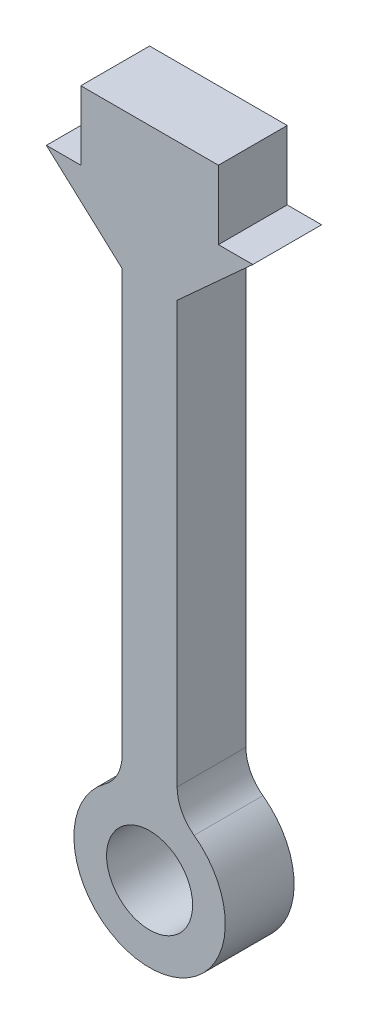
SolidWorks part; units mm, degrees
ref_plane "Plan de face" through (0, 0, 0) normal (0, 0, 1) x (1, 0, 0)
ref_plane "Plan de dessus" through (0, 0, 0) normal (0, 1, 0) x (1, 0, 0)
ref_plane "Plan de droite" through (0, 0, 0) normal (1, 0, 0) x (0, 0, -1)
sketch "Esquisse1" plane through (0, 0, 0) normal (0, 0, 1) x (1, 0, 0)
  line L0 (-1.6016, -1.3723) -> (4.3984, -1.3723)
  line L1 (-1.6016, -1.3723) -> (0.5984, -3.3723)
  line L2 (0.5984, -3.3723) -> (2.1984, -3.3723)
  line L3 (2.1984, -3.3723) -> (4.3984, -1.3723)
  line L4 (1.3984, 0.6277) -> (1.3984, -1.3723) construction
  line L5 (-0.6016, -1.3723) -> (3.3984, -1.3723)
  line L6 (-0.6016, -1.3723) -> (-0.6016, 0.6277)
  line L7 (-0.6016, 0.6277) -> (3.3984, 0.6277)
  line L8 (3.3984, -1.3723) -> (3.3984, 0.6277)
  line L10 (0.5984, -3.3723) -> (2.1984, -3.3723)
  line L11 (0.5984, -3.3723) -> (0.5984, -18.3723)
  line L12 (0.5984, -18.3723) -> (2.1984, -18.3723)
  line L13 (2.1984, -3.3723) -> (2.1984, -18.3723)
  circle A0 centre (1.3984, -18.3723) radius 2.2
  circle A1 centre (1.3984, -18.3723) radius 1.25
  dimension "D7" = 2.5
  dimension "D8" = 4.4
  dimension "D1" = 6
  dimension "D2" = 1.6
  dimension "D3" = 2
  dimension "D4" = 4
  dimension "D5" = 2
  dimension "D6" = 15
extrude "Boss.-Extru.1" add sketch "Esquisse1" along normal blind 2 contours A0 L13 L2 L11 | L2 L3 L0 L5 L1 | L7 L4 L5 L8 | L4 L7 L6 L0 | A1 L13 A0 L11 | A1 L11 A0 L13
fillet "Congé1" radius 1.2 2 edges at (0.5984, -16.3229, 1) (2.1984, -16.3229, 1)
